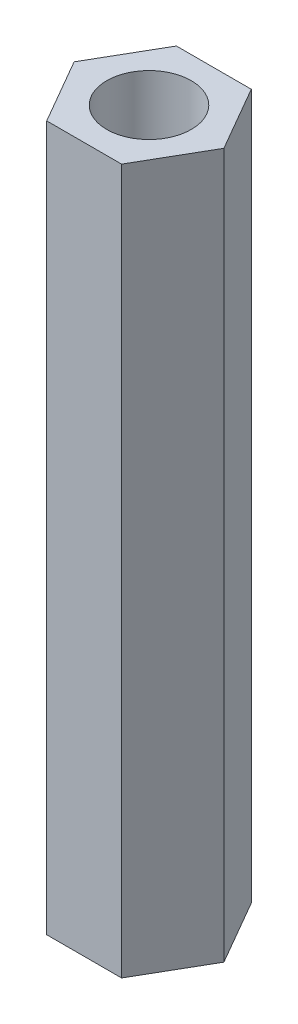
SolidWorks part; units mm, degrees
ref_plane "前视基准面" through (0, 0, 0) normal (0, 0, 1) x (1, 0, 0)
ref_plane "上视基准面" through (0, 0, 0) normal (0, 1, 0) x (1, 0, 0)
ref_plane "右视基准面" through (0, 0, 0) normal (1, 0, 0) x (0, 0, -1)
other "Configuration Table"
sketch "草图1" plane through (0, 0, 0) normal (0, 1, 0) x (1, 0, 0)
  line L1 (2.6558, 0) -> (1.3279, 2.3)
  line L2 (1.3279, 2.3) -> (-1.3279, 2.3)
  line L3 (-1.3279, 2.3) -> (-2.6558, 0)
  line L4 (-2.6558, 0) -> (-1.3279, -2.3)
  line L5 (-1.3279, -2.3) -> (1.3279, -2.3)
  line L6 (1.3279, -2.3) -> (2.6558, 0)
  circle A0 centre (0, 0) radius 2.3 construction
  circle A1 centre (0, 0) radius 1.5
  dimension "D1" = 4.6
  dimension "D2" = 3
extrude "凸台-拉伸1" add sketch "草图1" along normal blind 25
